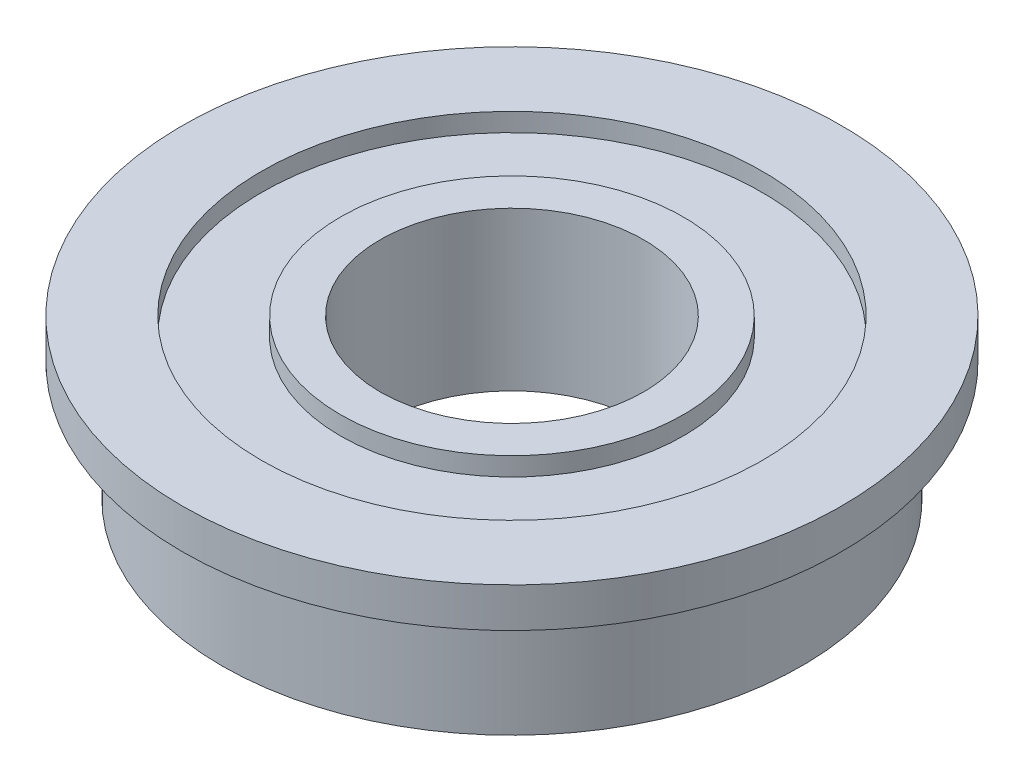
SolidWorks part; units mm, degrees
ref_plane "前视基准面" through (0, 0, 0) normal (0, 0, 1) x (1, 0, 0)
ref_plane "上视基准面" through (0, 0, 0) normal (0, 1, 0) x (1, 0, 0)
ref_plane "右视基准面" through (0, 0, 0) normal (1, 0, 0) x (0, 0, -1)
other "Configuration Table"
sketch "草图1" plane through (0, 0, 0) normal (0, 0, 1) x (1, 0, 0)
  line L0 (0, 4.6113) -> (0, -3.0029) construction
  line L1 (5, 6) -> (5, 0)
  line L2 (5, 0) -> (6.5, 0)
  line L3 (6.5, 0) -> (6.5, 0.7)
  line L4 (6.5, 0.7) -> (9.5, 0.7)
  line L5 (9.5, 0.7) -> (9.5, 0)
  line L6 (9.5, 0) -> (11, 0)
  line L7 (11, 0) -> (11, 6)
  line L8 (11, 6) -> (9.5, 6)
  line L9 (9.5, 6) -> (9.5, 5.3)
  line L10 (9.5, 5.3) -> (6.5, 5.3)
  line L11 (6.5, 5.3) -> (6.5, 6)
  line L12 (6.5, 6) -> (5, 6)
  dimension "D1" = 5
  dimension "D2" = 11
  dimension "D3" = 6
  dimension "D4" = 1.5
  dimension "D5" = 1.5
  dimension "D6" = 0.7
  dimension "D7" = 0.7
revolve "旋转1" add sketch "草图1" angle 360 about L0
sketch "草图2" plane through (0, 6, 0) normal (0, 1, 0) x (1, 0, 0)
  circle A0 centre (0, 0) radius 12.5
  circle A2 centre (0, 0) radius 11
  dimension "D1" = 25
extrude "凸台-拉伸1" add sketch "草图2" against normal blind 1.5
